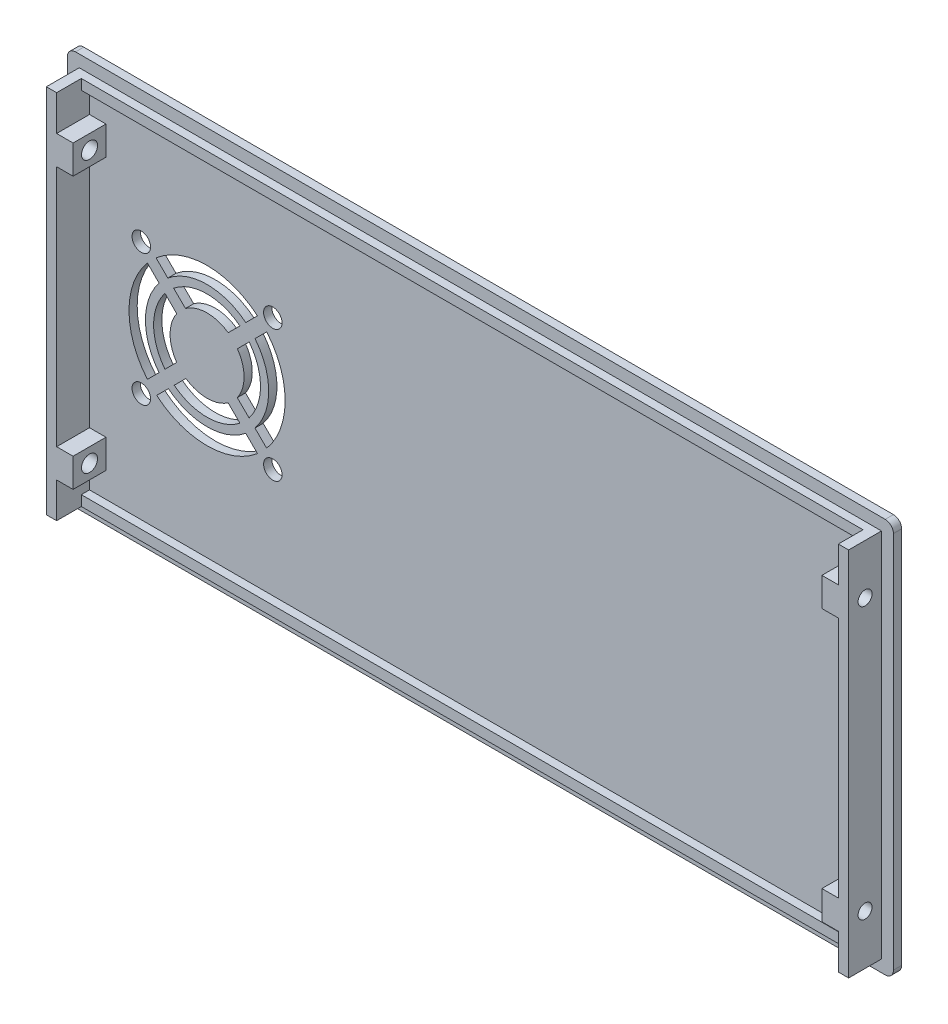
SolidWorks part; units mm, degrees
ref_plane "Přední rovina" through (0, 0, 0) normal (0, 0, 1) x (1, 0, 0)
ref_plane "Horní rovina" through (0, 0, 0) normal (0, 1, 0) x (1, 0, 0)
ref_plane "Pravá rovina" through (0, 0, 0) normal (1, 0, 0) x (0, 0, -1)
sketch "půdorys" plane through (0, 0, 0) normal (0, 0, 1) x (1, 0, 0)
  line L1 (-100.5, 48) -> (100.5, 48)
  line L2 (-100.5, 48) -> (-100.5, -48)
  line L3 (-100.5, -48) -> (100.5, -48)
  line L4 (100.5, 48) -> (100.5, -48)
  line L5 (-100.5, 48) -> (100.5, -48) construction
  line L6 (-100.5, -48) -> (100.5, 48) construction
  point P0 (0, 0)
  dimension "D1" = 201
  dimension "D2" = 96
extrude "Přidat vysunutím1" add sketch "půdorys" along normal blind 2
fillet "Zaoblit1" radius 2 4 edges at (-100.5, 48, 1) (-100.5, -48, 1) (100.5, -48, 1) (100.5, 48, 1)
sketch "Skica2" plane through (0, 0, 2) normal (0, 0, 1) x (1, 0, 0)
  line L0 (95.1, -42.6) -> (95.1, 42.6)
  line L1 (97.6, -45.1) -> (-97.6, -45.1)
  line L2 (97.6, -45.1) -> (97.6, 45.1)
  line L3 (97.6, 45.1) -> (-97.6, 45.1)
  line L4 (-97.6, -45.1) -> (-97.6, 45.1)
  line L5 (97.6, -45.1) -> (-97.6, 45.1) construction
  line L6 (97.6, 45.1) -> (-97.6, -45.1) construction
  line L7 (95.1, 42.6) -> (-95.1, 42.6)
  line L8 (-95.1, -42.6) -> (-95.1, 42.6)
  line L9 (95.1, -42.6) -> (-95.1, -42.6)
  line L10 (-95.1, 0) -> (0, 0)
  line L11 (0, 0) -> (0, -42.6)
  line L12 (-95.1, 36.5) -> (-91.1, 36.5)
  line L13 (-91.1, 36.5) -> (-91.1, 29.5)
  line L14 (-95.1, 29.5) -> (-91.1, 29.5)
  line L15 (-95.1, 3.5) -> (-95.1, -3.5)
  line L16 (95.1, -36.5) -> (91.1, -36.5)
  line L17 (91.1, -36.5) -> (91.1, -29.5)
  line L18 (95.1, -29.5) -> (91.1, -29.5)
  line L19 (95.1, 29.5) -> (91.1, 29.5)
  line L20 (95.1, 36.5) -> (91.1, 36.5)
  line L21 (-91.1, -33) -> (-95.1, -33)
  line L22 (-95.1, -36.5) -> (-91.1, -36.5)
  line L23 (-95.1, -36.5) -> (-95.1, -29.5)
  line L24 (-95.1, -29.5) -> (-91.1, -29.5)
  line L25 (-91.1, -36.5) -> (-91.1, -29.5)
  line L26 (91.1, 36.5) -> (91.1, 29.5)
  point P0 (0, 0)
  point P14 (-93.1, 0)
  point P16 (0, 0)
  point P17 (0, 0)
  point P19 (0, 0)
  dimension "D1" = 2.9
  dimension "D2" = 2.9
  dimension "D6" = 15
  dimension "D7" = 7
  dimension "D8" = 4
  dimension "D3" = 2.5
extrude "Přidat vysunutím2" add sketch "Skica2" along normal blind 2 contours L4 L1 L2 L3 L0 L9 L8 L7 | L0 L18 L17 L16 | L20 L26 L19 L0 | L8 L14 L13 L12 | L24 L25 L22 L23
sketch "Skica3" plane through (0, 0, 4) normal (0, 0, 1) x (1, 0, 0)
  line L0 (95.1, 42.6) -> (95.1, 45.1)
  line L1 (97.6, 45.1) -> (-97.6, 45.1) construction
  line L2 (97.6, -45.1) -> (97.6, 45.1) construction
  line L3 (97.6, 45.1) -> (95.1, 45.1)
  line L4 (95.1, -42.6) -> (95.1, -45.1)
  line L5 (95.1, -3.5) -> (95.1, 3.5)
  line L11 (97.6, -45.1) -> (-97.6, -45.1) construction
  line L12 (95.1, -45.1) -> (97.6, -45.1)
  line L13 (0, -42.6) -> (0, 45.1)
  line L14 (95.1, -42.6) -> (-95.1, -42.6) construction
  line L15 (-95.1, -45.1) -> (-97.6, -45.1)
  line L16 (-95.1, -3.5) -> (-95.1, -45.1)
  line L17 (-95.1, 3.5) -> (-95.1, -3.5)
  line L20 (-95.1, 45.1) -> (-95.1, 3.5)
  line L21 (-97.6, -45.1) -> (-97.6, 45.1)
  line L22 (-97.6, 45.1) -> (-95.1, 45.1)
extrude "Přidat vysunutím3" add sketch "Skica3" along normal blind 6
sketch "Skica4" plane through (-91.1, 0, 0) normal (1, 0, 0) x (0, 0, -1)
  line L0 (-10, 33) -> (-2, 33)
  line L1 (-10, 29.5) -> (-10, 36.5) construction
  line L2 (-2, 36.5) -> (-2, 29.5) construction
  line L3 (0, 0) -> (39.445, 0)
  point P14 (-6, 33)
  point P15 (-6, -33)
hole_wizard "Válcové zahloubení pro M6 šrouby s válcovou hlavou zaoblenou1" positions "3DSkica1" profile "Skica6" counterbore size "M6" standard "ANSI Metric"
sketch3d "3DSkica1"
  point P3 (-91.1, 33, 6)
  point P9 (-91.1, -33, 6)
sketch "Skica6" plane through (-91.1, 33, 6) normal (0, 1, 0) x (0, 0, -1)
  line L0 (0, 0) -> (0, 9.4)
  line L1 (0, 9.4) -> (1.7, 9.4)
  line L3 (1.7, 9.4) -> (1.7, 4)
  line L4 (1.7, 4) -> (1.95, 4)
  line L5 (1.95, 4) -> (1.95, 0)
  line L7 (1.95, 0) -> (0, 0)
  line L11 (0, -6.35) -> (0, 107.95) construction
  dimension "Průměr díry skrz" = 3.4
  dimension "Hloubka díry skrz" = 9.4
  dimension "Průměr válcového zahloubení" = 3.9
  dimension "Hloubka válcového zahloubení" = 4
ref_plane "Rovina1" through (0, 0, 0) normal (1, 0, 0) x (0, 0, -1)
mirror "Zrcadlit1" about plane through (0, 0, 0) normal (1, 0, 0) of "Válcové zahloubení pro M6 šrouby s válcovou hlavou zaoblenou1"
sketch "Skica7" plane through (0, 0, 0) normal (0, 0, -1) x (-1, 0, 0)
  line L0 (100.5, 0) -> (-100.5, 0)
  line L1 (100.5, 46) -> (100.5, -46) construction
  line L2 (-100.5, -46) -> (-100.5, 46) construction
  line L3 (82.5, -16) -> (50.5, 16)
  line L4 (82.5, -16) -> (50.5, -16)
  line L5 (82.5, -16) -> (82.5, 16)
  line L6 (82.5, 16) -> (50.5, 16)
  line L7 (50.5, -16) -> (50.5, 16)
  line L8 (82.5, -16) -> (50.5, 16) construction
  line L9 (82.5, 16) -> (50.5, -16) construction
  line L10 (80.25, -16) -> (48.25, 16)
  line L11 (84.75, -16) -> (52.75, 16)
  line L12 (50.5, -16) -> (49.5002, -16.0176)
  line L13 (50.5, -16) -> (49.5001, -15.9828)
  line L14 (82.5, 16) -> (80.5003, 15.9648)
  line L15 (50.5, -13.75) -> (80.5003, 15.9648)
  line L16 (52.75, -16) -> (82.5, 13.75)
  line L17 (82.5, -16) -> (83.1871, -15.2735)
  line L18 (82.5, -16) -> (81.5001, -16.0172)
  line L19 (50.5, 16) -> (13.6513, 19.6513)
  line L20 (50.5, 16) -> (5.7505, 11.7505)
  circle A0 centre (66.5, 0) radius 9
  circle A1 centre (82.5, -16) radius 2.25
  circle A2 centre (50.5, -16) radius 2.25
  circle A3 centre (50.5, 16) radius 2.25
  circle A4 centre (82.5, 16) radius 2.25
  circle A5 centre (66.5, 0) radius 13
  circle A6 centre (66.5, 0) radius 15
  circle A7 centre (66.5, 0) radius 19
  dimension "D2" = 18
  dimension "D5" = 4.5
  dimension "D1" = 34
  dimension "D4" = 32
  dimension "D10" = 1
  dimension "D11" = 1
  dimension "D6" = 4
  dimension "D7" = 2
  dimension "D8" = 4
extrude "Odebrat vysunutím1" cut sketch "Skica7" against normal blind 6 contours L0 A7 L5 | L5 A7 L16 A6 L0 | L15 A7 L6 L11 A6 | L6 A7 | L10 A7 L7 L0 A6 | L7 A7 L0 | L0 A7 L7 | L7 A7 L15 A6 L0 | L16 A7 L4 L10 A6 | L4 A7 | L11 A7 L5 L0 A6 | L5 A7 L0 | L11 A5 L0 A0 | L16 A5 L10 A0 | L0 A5 L15 A0 | L10 A5 L0 A0 | L15 A5 L11 A0 | L0 A5 L16 A0 | A2 | A1 | A4 | A3
